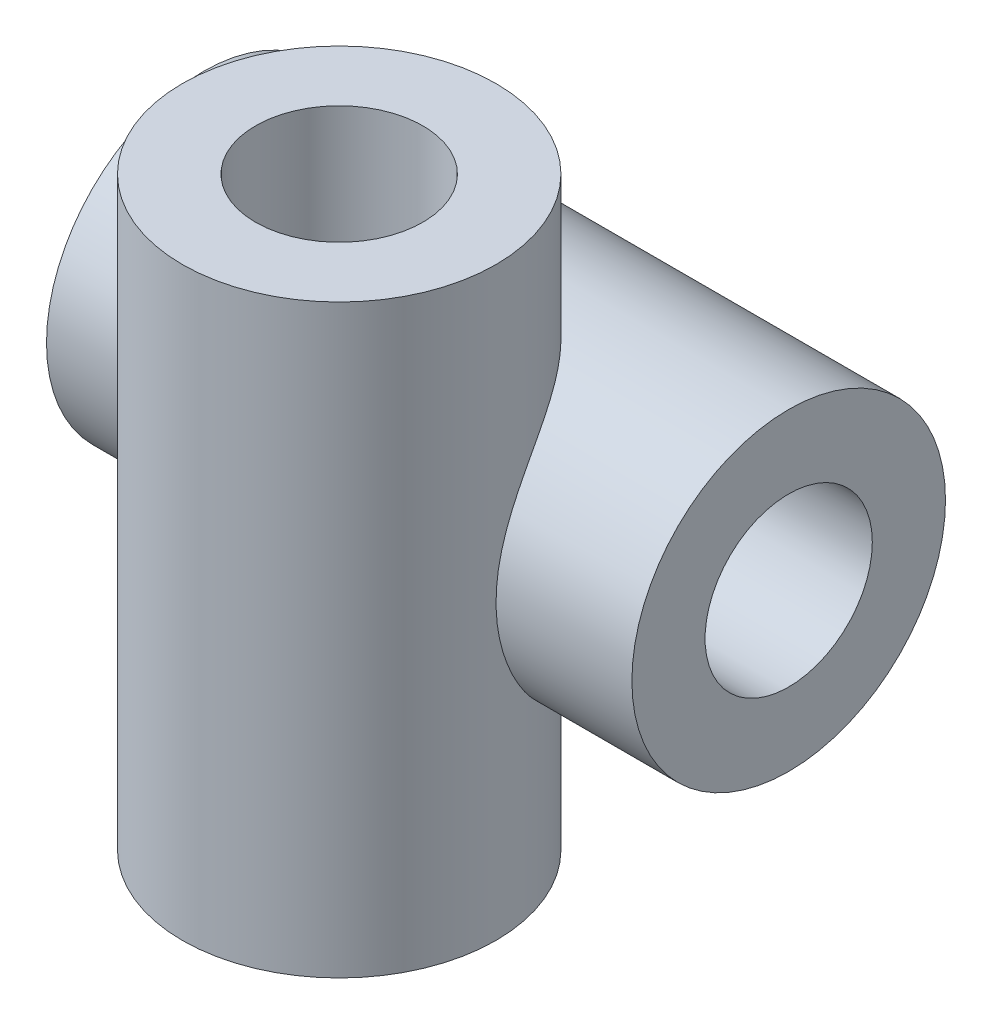
SolidWorks part; units mm, degrees
ref_plane "Front Plane" through (0, 0, 0) normal (0, 0, 1) x (1, 0, 0)
ref_plane "Top Plane" through (0, 0, 0) normal (0, 1, 0) x (1, 0, 0)
ref_plane "Right Plane" through (0, 0, 0) normal (1, 0, 0) x (0, 0, -1)
sketch "Sketch1" plane through (0, 0, 0) normal (0, 1, 0) x (1, 0, 0)
  circle A0 centre (0, 0) radius 15
  circle A1 centre (0, 0) radius 8
  dimension "D1" = 30
  dimension "D2" = 16
extrude "Boss-Extrude1" add sketch "Sketch1" along normal mid plane 56
sketch "Sketch2" plane through (0, 0, 0) normal (1, 0, 0) x (0, 0, -1)
  line L0 (15, -28) -> (15, 28) construction
  circle A0 centre (15, 0) radius 15
  circle A1 centre (15, 0) radius 8
  dimension "D1" = 30
  dimension "D2" = 16
extrude "Boss-Extrude2" add sketch "Sketch2" along normal mid plane 56
sketch "Sketch3" plane through (0, 28, 0) normal (0, 1, 0) x (1, 0, 0)
  circle A0 centre (0, 0) radius 8 construction
  circle A1 centre (0, 0) radius 8
extrude "Cut-Extrude1" cut sketch "Sketch3" against normal through all
sketch "Sketch4" plane through (28, 0, 0) normal (1, 0, 0) x (0, 0, -1)
  circle A0 centre (15, 0) radius 8 construction
  circle A1 centre (15, 0) radius 8
extrude "Cut-Extrude2" cut sketch "Sketch4" against normal through all
